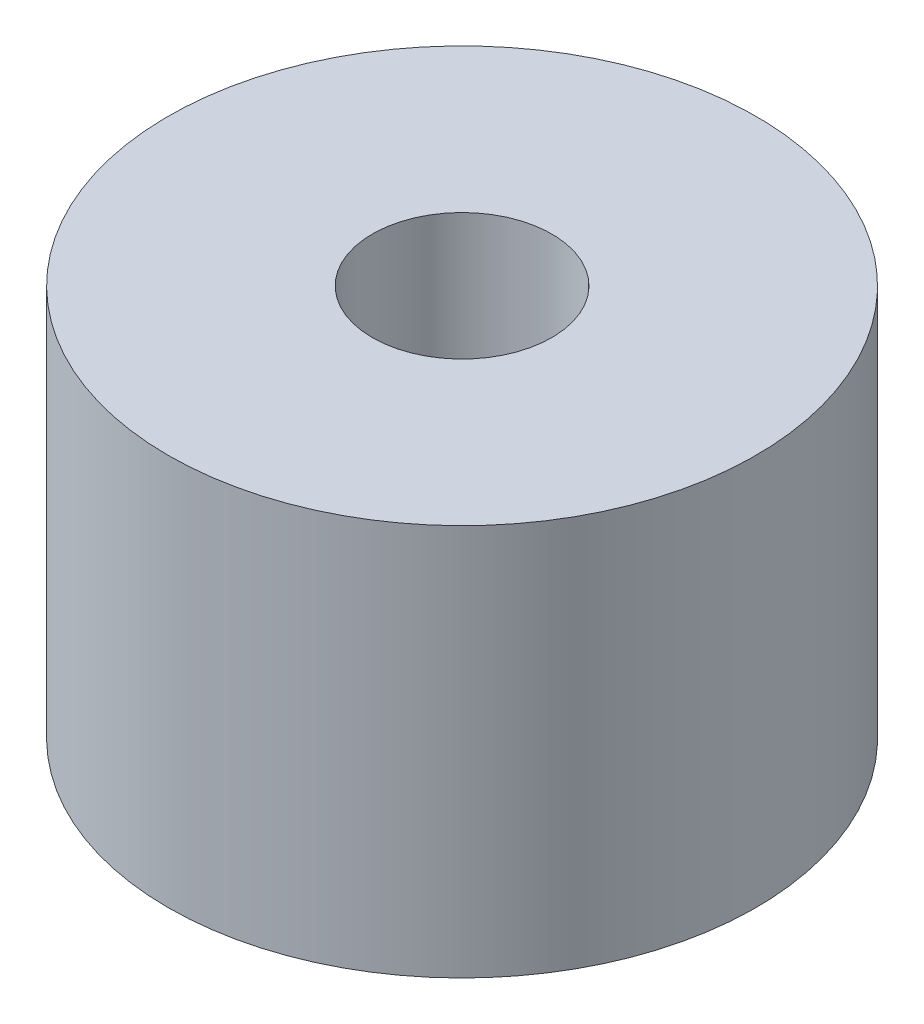
SolidWorks part; units mm, degrees
ref_plane "Front Plane" through (0, 0, 0) normal (0, 0, 1) x (1, 0, 0)
ref_plane "Top Plane" through (0, 0, 0) normal (0, 1, 0) x (1, 0, 0)
ref_plane "Right Plane" through (0, 0, 0) normal (1, 0, 0) x (0, 0, -1)
sketch "Sketch1" plane through (0, 0, 0) normal (0, 1, 0) x (1, 0, 0)
  circle A0 centre (0, 0) radius 18
  circle A1 centre (0, 0) radius 5.5
  dimension "D1" = 36
  dimension "D2" = 11
extrude "Boss-Extrude1" add sketch "Sketch1" along normal blind 24
